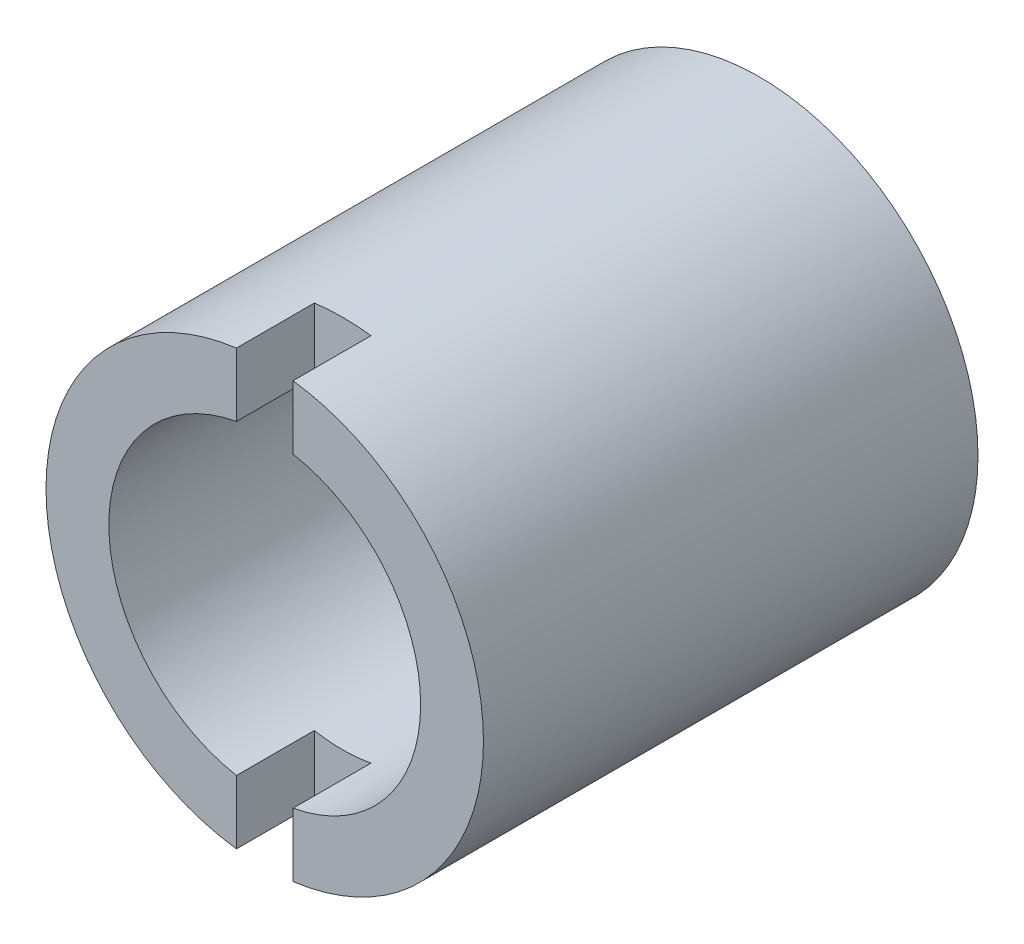
SolidWorks part; units mm, degrees
material "2.0321 (CuZn37)"
ref_plane "Alzado" through (0, 0, 0) normal (0, 0, 1) x (1, 0, 0)
ref_plane "Planta" through (0, 0, 0) normal (0, 1, 0) x (1, 0, 0)
ref_plane "Vista lateral" through (0, 0, 0) normal (1, 0, 0) x (0, 0, -1)
sketch "Croquis1" plane through (0, 0, 0) normal (0, 0, 1) x (1, 0, 0)
  circle A0 centre (0, 0) radius 6.5
  dimension "D1" = 13
extrude "Extruir-Lámina1" add sketch "Croquis1" against normal blind 20.62 thin
sketch "Croquis2" plane through (0, 0, 0) normal (0, 0, 1) x (1, 0, 0)
  line L5 (-1.18, -10) -> (1.18, -10)
  line L6 (-1.18, -10) -> (-1.18, 10)
  line L7 (-1.18, 10) -> (1.18, 10)
  line L8 (1.18, -10) -> (1.18, 10)
  line L9 (-1.18, -10) -> (1.18, 10) construction
  line L10 (-1.18, 10) -> (1.18, -10) construction
  point P0 (0, 0)
  point P1 (0, 0)
  dimension "D1" = 2.36
  dimension "D2" = 20
extrude "Cortar-Extruir1" cut sketch "Croquis2" against normal blind 3.25
